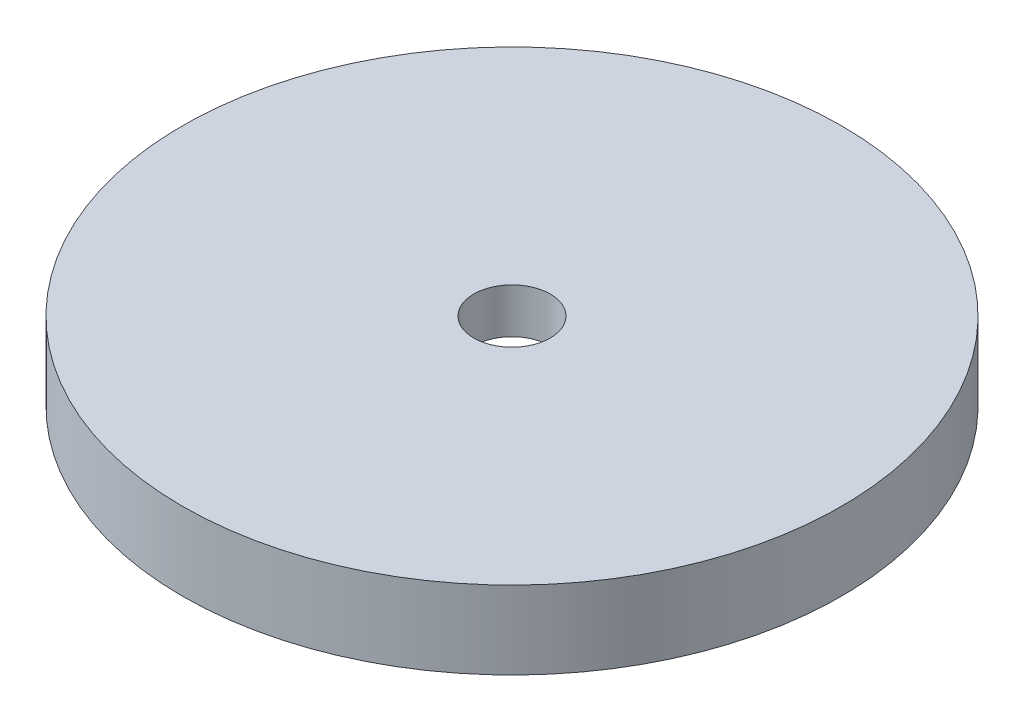
SolidWorks part; units mm, degrees
material "PVC Rigid"
ref_plane "Front Plane" through (0, 0, 0) normal (0, 0, 1) x (1, 0, 0)
ref_plane "Top Plane" through (0, 0, 0) normal (0, 1, 0) x (1, 0, 0)
ref_plane "Right Plane" through (0, 0, 0) normal (1, 0, 0) x (0, 0, -1)
sketch "Sketch1" plane through (0, 0, 0) normal (0, 1, 0) x (1, 0, 0)
  circle A0 centre (0, 0) radius 22
  circle A1 centre (0, 0) radius 2.55
  dimension "D1" = 44
  dimension "D2" = 5.1
extrude "Boss-Extrude1" add sketch "Sketch1" along normal blind 5.2
sketch "Sketch2" plane through (0, 0, 0) normal (0, -1, 0) x (1, 0, 0)
  circle A0 centre (0, 0) radius 21
extrude "Cut-Extrude1" cut sketch "Sketch2" against normal blind 2.2
